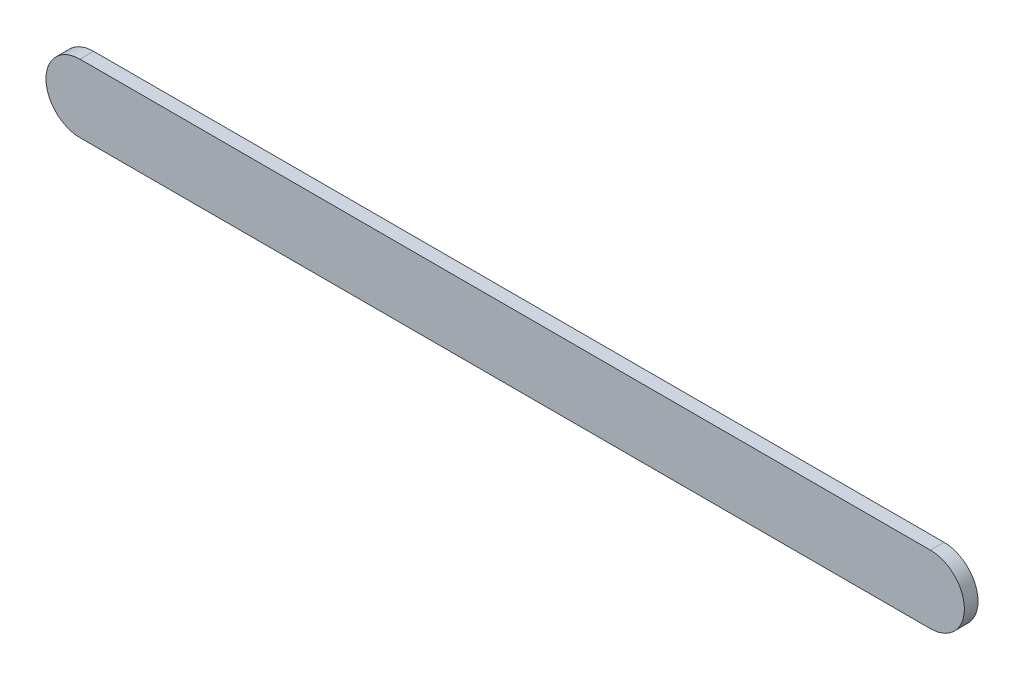
SolidWorks part; units mm, degrees
ref_plane "Front Plane" through (0, 0, 0) normal (0, 0, 1) x (1, 0, 0)
ref_plane "Top Plane" through (0, 0, 0) normal (0, 1, 0) x (1, 0, 0)
ref_plane "Right Plane" through (0, 0, 0) normal (1, 0, 0) x (0, 0, -1)
sketch "Sketch1" plane through (0, 0, 0) normal (0, 0, 1) x (1, 0, 0)
  line L0 (0, 0) -> (125, 0) construction
  line L1 (0, 5) -> (125, 5)
  line L2 (0, -5) -> (125, -5)
  arc A0 (0, 5) -> (0, -5) centre (0, 0) ccw
  arc A1 (125, -5) -> (125, 5) centre (125, 0) ccw
  point P3 (62.5, 0)
  dimension "D1" = 5
  dimension "D2" = 125
extrude "Boss-Extrude1" add sketch "Sketch1" along normal mid plane 2
